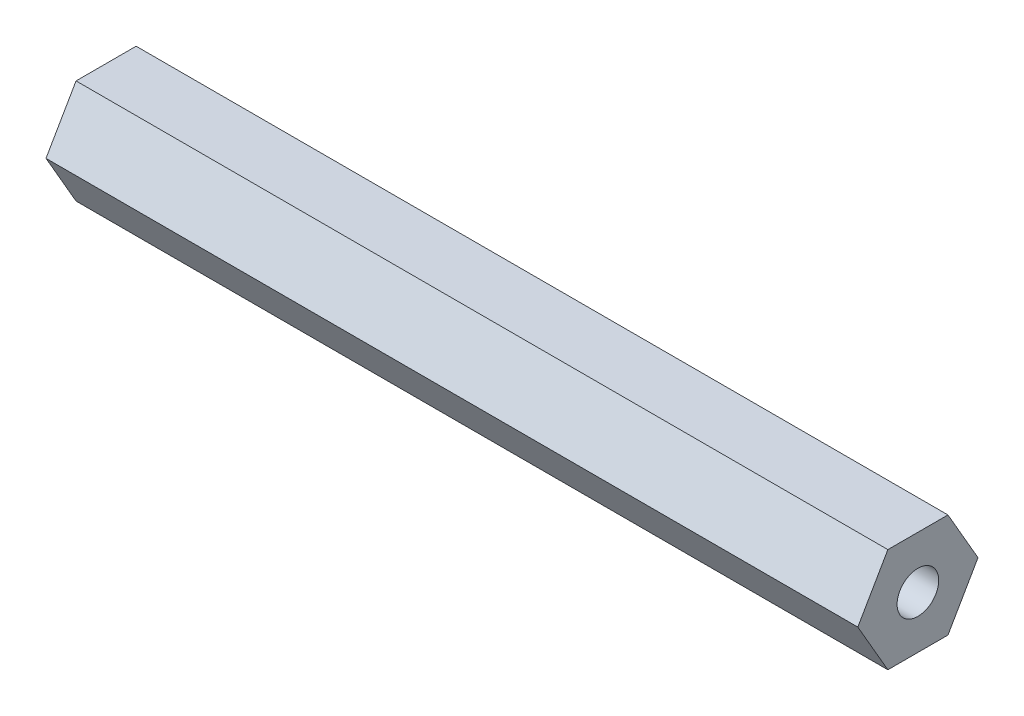
SolidWorks part; units mm, degrees
material "7075-T6 (SN)"
ref_plane "前视基准面" through (0, 0, 0) normal (0, 0, 1) x (1, 0, 0)
ref_plane "上视基准面" through (0, 0, 0) normal (0, 1, 0) x (1, 0, 0)
ref_plane "右视基准面" through (0, 0, 0) normal (1, 0, 0) x (0, 0, -1)
other "Configuration Table"
sketch "草图1" plane through (0, 0, 0) normal (1, 0, 0) x (0, 0, -1)
  line L1 (2.8868, 0) -> (1.4434, 2.5)
  line L2 (1.4434, 2.5) -> (-1.4434, 2.5)
  line L3 (-1.4434, 2.5) -> (-2.8868, 0)
  line L4 (-2.8868, 0) -> (-1.4434, -2.5)
  line L5 (-1.4434, -2.5) -> (1.4434, -2.5)
  line L6 (1.4434, -2.5) -> (2.8868, 0)
  circle A0 centre (0, 0) radius 2.5 construction
  circle A1 centre (0, 0) radius 1
  dimension "D1" = 5
  dimension "D2" = 2
extrude "凸台-拉伸1" add sketch "草图1" along normal blind 39
